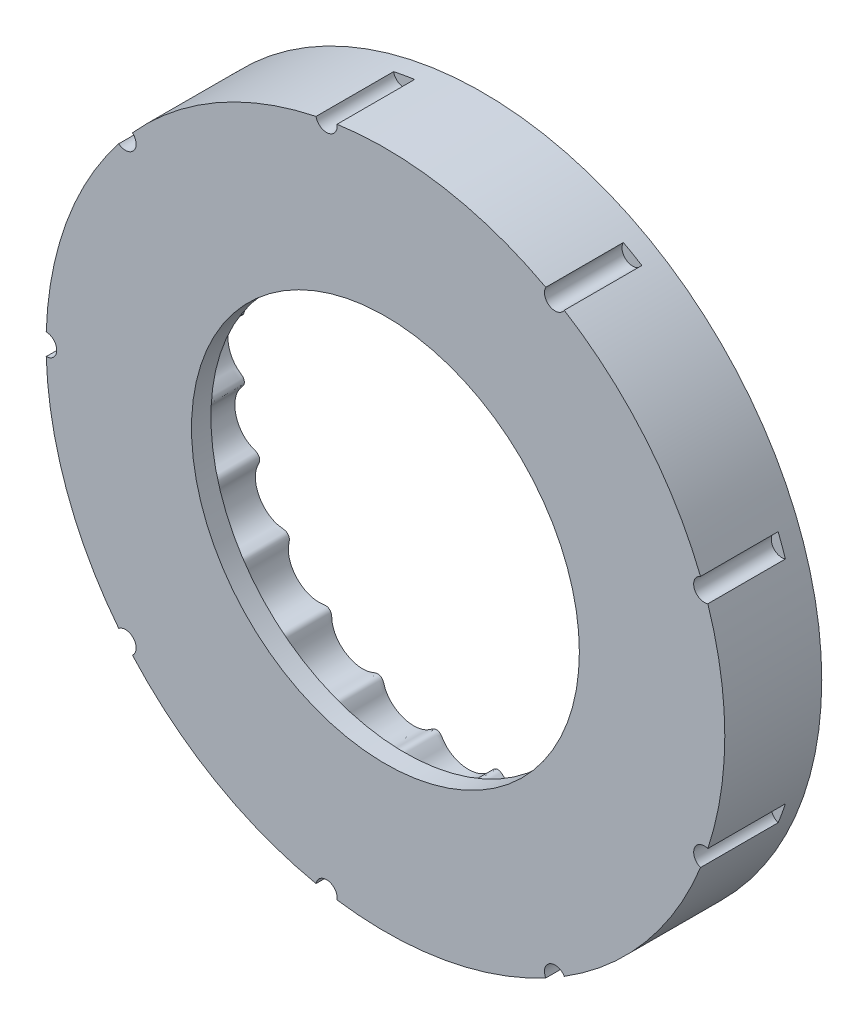
SolidWorks part; units mm, degrees
ref_plane "Plan de face" through (0, 0, 0) normal (0, 0, 1) x (1, 0, 0)
ref_plane "Plan de dessus" through (0, 0, 0) normal (0, 1, 0) x (1, 0, 0)
ref_plane "Plan de droite" through (0, 0, 0) normal (1, 0, 0) x (0, 0, -1)
sketch "Esquisse1" plane through (0, 0, 0) normal (0, 0, 1) x (1, 0, 0)
  line L0 (-1000, 0) -> (49000, 0) construction
  circle A1 centre (0, 0) radius 35
  spline S0 degree 4 poles (24.1426, 6.7991) (24.1177, 6.7609) (24.0692, 6.6836) (24.0004, 6.5645) (23.9483, 6.387) (23.9505, 6.1855) (24.0272, 5.9803) (24.1778, 5.8151) (24.3705, 5.7045) (24.5983, 5.5844) (24.8479, 5.4264) (25.1139, 5.2067) (25.3819, 4.9129) (25.6102, 4.583) (25.7961, 4.2235) (25.9371, 3.8403) (26.0305, 3.4429) (26.0756, 3.0373) (26.0716, 2.6291) (26.0179, 2.2244) (25.9151, 1.834) (25.7643, 1.4641) (25.5917, 1.1641) (25.4167, 0.9296) (25.2526, 0.7496) (25.1124, 0.6144) (24.9828, 0.4987) (24.8797, 0.3844) (24.8179, 0.2829) (24.7848, 0.2051) (24.7673, 0.1461) (24.7588, 0.1043) (24.7529, 0.0597) (24.7496, 0.0145) (24.7496, -0.0147) (24.7529, -0.06) (24.7589, -0.1048) (24.7675, -0.1468) (24.7852, -0.2061) (24.8185, -0.2842) (24.8808, -0.3859) (24.9847, -0.5005) (25.1148, -0.6166) (25.2554, -0.7525) (25.4198, -0.9333) (25.595, -1.1691) (25.7689, -1.4729) (25.9207, -1.8497) (26.0235, -2.2499) (26.0747, -2.6669) (26.0733, -3.0863) (26.0204, -3.5015) (25.917, -3.9063) (25.7644, -4.2943) (25.5662, -4.6548) (25.3259, -4.9815) (25.0816, -5.2331) (24.8519, -5.4186) (24.6671, -5.5402) (24.5395, -5.6139) (24.4102, -5.6846) (24.274, -5.758) (24.12, -5.8678) (23.9899, -6.0503) (23.9364, -6.2751) (23.9692, -6.4958) (24.0654, -6.6843) (24.1784, -6.8519) (24.2801, -7.019) (24.3936, -7.2353) (24.5034, -7.5077) (24.5951, -7.8454) (24.647, -8.2482) (24.6457, -8.6612) (24.576, -9.1855) (24.4176, -9.6961) (24.1747, -10.1766) (23.852, -10.6101) (23.5588, -10.9098) (23.241, -11.1578) (22.9466, -11.3291) (22.6921, -11.4408) (22.4727, -11.5135) (22.2939, -11.5615) (22.1013, -11.606) (21.9021, -11.6816) (21.7285, -11.8281) (21.6209, -12.0388) (21.6016, -12.2637) (21.6505, -12.4693) (21.7183, -12.6598) (21.7746, -12.8471) (21.8297, -13.085) (21.8672, -13.3762) (21.8707, -13.726) (21.8195, -14.1287) (21.7142, -14.528) (21.5148, -15.0178) (21.2331, -15.4721) (20.8771, -15.876) (20.4557, -16.2144) (20.0964, -16.4307) (19.7262, -16.5906) (19.3981, -16.6821) (19.1236, -16.7259) (18.8929, -16.7409) (18.7078, -16.7424) (18.5101, -16.7378) (18.2984, -16.7644) (18.0955, -16.8669) (17.9421, -17.0472) (17.8714, -17.2614) (17.8702, -17.4725) (17.8883, -17.6738) (17.8957, -17.8692) (17.8889, -18.1133) (17.8517, -18.4044) (17.7668, -18.7438) (17.6158, -19.1205) (17.4134, -19.4803) (17.1623, -19.8168) (16.8685, -20.1221) (16.5358, -20.3908) (16.1684, -20.6173) (15.771, -20.7957) (15.3688, -20.9145) (14.9702, -20.976) (14.6296, -20.9817) (14.3529, -20.9549) (14.1259, -20.9112) (13.9464, -20.866) (13.7558, -20.8128) (13.5435, -20.7889) (13.3222, -20.8417) (13.1314, -20.9817) (13.013, -21.1736) (12.9618, -21.3782) (12.9291, -21.5776) (12.887, -21.7685) (12.8188, -22.0029) (12.7093, -22.2752) (12.5416, -22.5821) (12.3006, -22.9086) (12.0142, -23.2057) (11.6866, -23.4682) (11.3255, -23.6897) (10.9359, -23.8661) (10.5233, -23.9928) (10.0937, -24.0655) (9.6744, -24.0792) (9.2731, -24.0382) (8.942, -23.9578) (8.6811, -23.862) (8.4724, -23.7624) (8.31, -23.6735) (8.1383, -23.575) (7.9372, -23.5018) (7.7049, -23.5021) (7.4781, -23.6007) (7.3169, -23.7729) (7.2208, -23.9706) (7.1156, -24.2034) (6.9743, -24.4604) (6.773, -24.7375) (6.4979, -25.0224) (6.1834, -25.2709) (5.8357, -25.4797) (5.4603, -25.6452) (5.0615, -25.7656) (4.6447, -25.8371) (4.2157, -25.8559) (3.7816, -25.8181) (3.3723, -25.7258) (2.9942, -25.5849) (2.6941, -25.4236) (2.4656, -25.2649) (2.2891, -25.1158) (2.1537, -24.9891) (2.0123, -24.8511) (1.8324, -24.7331) (1.553, -24.6659) (1.2621, -24.7546) (1.0754, -24.9576) (0.8891, -25.1941) (0.6967, -25.4018) (0.4476, -25.6153) (0.1257, -25.8218) (-0.2246, -25.9871) (-0.599, -26.1091) (-0.9909, -26.1853) (-1.3919, -26.2146) (-1.7962, -26.1958) (-2.1981, -26.1285) (-2.5915, -26.0119) (-2.9628, -25.849) (-3.3062, -25.6424) (-3.6154, -25.3948) (-3.8503, -25.1456) (-4.0231, -24.9087) (-4.157, -24.6911) (-4.2763, -24.5066) (-4.4563, -24.3545) (-4.6931, -24.2829) (-4.9238, -24.3097) (-5.115, -24.4061) (-5.2732, -24.5252) (-5.423, -24.6339) (-5.6174, -24.7592) (-5.864, -24.8876) (-6.1822, -25.0094) (-6.5751, -25.1011) (-6.9928, -25.1407) (-7.4281, -25.1231) (-7.8512, -25.0501) (-8.2556, -24.9263) (-8.636, -24.7563) (-8.9874, -24.5444) (-9.3058, -24.2932) (-9.5861, -24.0067) (-9.8229, -23.6892) (-9.9872, -23.3887) (-10.0948, -23.1158) (-10.1696, -22.8715) (-10.2411, -22.6635) (-10.3812, -22.4737) (-10.595, -22.3493) (-10.8256, -22.322) (-11.0338, -22.3709) (-11.2164, -22.4474) (-11.3887, -22.5149) (-11.6084, -22.5872) (-11.8793, -22.649) (-12.2179, -22.6866) (-12.6212, -22.6763) (-13.0353, -22.6095) (-13.4521, -22.4829) (-13.8453, -22.3049) (-14.2094, -22.0805) (-14.5395, -21.815) (-14.8313, -21.5131) (-15.0777, -21.1819) (-15.2753, -20.8275) (-15.4026, -20.5017) (-15.4765, -20.2177) (-15.5143, -19.9765) (-15.5318, -19.7817) (-15.5392, -19.5798) (-15.5656, -19.3704) (-15.6608, -19.166) (-15.8341, -19.0047) (-16.0476, -18.9266) (-16.2611, -18.9252) (-16.4568, -18.9543) (-16.6405, -18.9763) (-16.8713, -18.9908) (-17.1491, -18.9822) (-17.4862, -18.9332) (-17.8737, -18.8216) (-18.2576, -18.6527) (-18.6291, -18.4253) (-18.9648, -18.1541) (-19.2607, -17.8454) (-19.5135, -17.5053) (-19.7199, -17.1396) (-19.875, -16.7569) (-19.9769, -16.364) (-20.018, -16.0166) (-20.0178, -15.7231) (-19.9934, -15.4801) (-19.9613, -15.2872) (-19.9181, -15.0898) (-19.894, -14.8799) (-19.9394, -14.6589) (-20.0707, -14.462) (-20.2602, -14.3367) (-20.4672, -14.2852) (-20.6639, -14.2651) (-20.8473, -14.2402) (-21.0742, -14.196) (-21.3408, -14.1175) (-21.6546, -13.985) (-22.0015, -13.7794) (-22.3304, -13.5193) (-22.7055, -13.1302) (-23.0074, -12.6844) (-23.2291, -12.1981) (-23.3648, -11.6869) (-23.4186, -11.2774) (-23.4182, -10.8714) (-23.3703, -10.5248) (-23.296, -10.2407) (-23.211, -10.0117) (-23.1314, -9.8331) (-23.0402, -9.6526) (-22.9672, -9.4541) (-22.9601, -9.2287) (-23.0424, -9.0072) (-23.1982, -8.8407) (-23.3889, -8.7414) (-23.5777, -8.6723) (-23.7531, -8.5999) (-23.9662, -8.4963) (-24.2093, -8.3477) (-24.4803, -8.1356) (-24.7613, -7.8463) (-25.0085, -7.5133) (-25.2666, -7.049) (-25.4429, -6.5476) (-25.5339, -6.0256) (-25.5366, -5.4989) (-25.4855, -5.0889) (-25.3828, -4.696) (-25.2489, -4.3726) (-25.1052, -4.1164) (-24.9652, -3.9162) (-24.8431, -3.7634) (-24.7098, -3.6112) (-24.5919, -3.4354) (-24.5338, -3.2206) (-24.5604, -2.9926) (-24.6667, -2.797) (-24.8227, -2.6537) (-24.9897, -2.5393) (-25.1463, -2.4221) (-25.3325, -2.2638) (-25.5023, -2.0873) (-25.6545, -1.8958) (-25.7905, -1.6883) (-25.89, -1.512) (-25.979, -1.3255) (-26.0566, -1.1315) (-26.1214, -0.9307) (-26.1732, -0.7298) (-26.2073, -0.5457) (-26.2284, -0.3959) (-26.2405, -0.2557) (-26.247, -0.1691) (-26.2503, -0.0328) (-26.2503, 0.0323) (-26.2471, 0.1679) (-26.2407, 0.2542) (-26.2286, 0.3933) (-26.2078, 0.5423) (-26.1742, 0.7251) (-26.123, 0.925) (-26.0591, 1.1245) (-25.9824, 1.3176) (-25.8737, 1.547) (-25.7224, 1.8046) (-25.5451, 2.0414) (-25.3437, 2.2529) (-25.1596, 2.4115) (-25.0044, 2.5289) (-24.8386, 2.6423) (-24.6804, 2.7808) (-24.5546, 2.9935) (-24.5303, 3.2355) (-24.6, 3.4498) (-24.7118, 3.6094) (-24.804, 3.7191) (-24.9086, 3.8447) (-25.0204, 3.9911) (-25.1376, 4.1713) (-25.2521, 4.3886) (-25.3469, 4.6153) (-25.4409, 4.9075) (-25.515, 5.269) (-25.5464, 5.6988) (-25.509, 6.1899) (-25.401, 6.6704) (-25.2688, 7.0153) (-25.1588, 7.235) (-25.0985, 7.3418) knots 0 0 0 0 0 0.001685 0.003369 0.005054 0.006738 0.009006 0.011274 0.013086 0.014899 0.018524 0.022149 0.025774 0.029532 0.03329 0.037047 0.040805 0.044562 0.048319 0.052076 0.055834 0.059425 0.063017 0.064813 0.066609 0.068405 0.070201 0.071231 0.072261 0.072776 0.073291 0.073548 0.073806 0.074321 0.074838 0.075097 0.075356 0.075873 0.07639 0.077425 0.07846 0.080263 0.082066 0.083868 0.085671 0.089277 0.092883 0.09675 0.100617 0.104484 0.108351 0.112188 0.116026 0.119864 0.123701 0.127327 0.130952 0.132764 0.134577 0.135483 0.13639 0.138202 0.140296 0.142389 0.144459 0.146528 0.148331 0.150133 0.151935 0.153737 0.157342 0.160946 0.164812 0.168678 0.172544 0.180416 0.184421 0.188427 0.192432 0.195844 0.199256 0.200962 0.202668 0.204374 0.20608 0.208269 0.210458 0.212527 0.214596 0.216398 0.2182 0.220001 0.221803 0.225407 0.22901 0.232875 0.23674 0.240605 0.248477 0.252483 0.256489 0.260496 0.263908 0.26732 0.269026 0.270732 0.272438 0.274144 0.276335 0.278527 0.280595 0.282663 0.284464 0.286266 0.288067 0.289868 0.293471 0.297074 0.300938 0.304802 0.308666 0.31253 0.316537 0.320545 0.324552 0.328559 0.331971 0.335384 0.33709 0.338796 0.340502 0.342208 0.344401 0.346595 0.348662 0.350729 0.35253 0.354331 0.356132 0.357933 0.361536 0.365138 0.369001 0.372864 0.376727 0.38059 0.384598 0.388606 0.392614 0.396623 0.400035 0.403448 0.405154 0.40686 0.408567 0.410273 0.412468 0.414663 0.416905 0.419148 0.420948 0.422747 0.426346 0.429946 0.433545 0.437321 0.441097 0.444873 0.44865 0.452659 0.456668 0.460677 0.464686 0.468099 0.471512 0.473218 0.474925 0.476631 0.478338 0.480534 0.48273 0.48702 0.488749 0.490478 0.493937 0.497395 0.500854 0.50453 0.508207 0.511883 0.515559 0.519335 0.523111 0.526887 0.530662 0.534262 0.537861 0.54146 0.543259 0.545059 0.547301 0.549542 0.551738 0.553933 0.55564 0.557346 0.559053 0.560759 0.564172 0.567585 0.571593 0.575602 0.57961 0.583619 0.587396 0.591172 0.594949 0.598726 0.602325 0.605924 0.609523 0.611323 0.613123 0.615366 0.61761 0.619804 0.621998 0.623704 0.625411 0.627117 0.628823 0.632235 0.635648 0.639656 0.643663 0.647671 0.651679 0.655542 0.659406 0.663269 0.667133 0.670735 0.674338 0.676139 0.67794 0.679742 0.681543 0.68361 0.685678 0.68787 0.690063 0.691769 0.693475 0.695181 0.696887 0.700299 0.703711 0.707718 0.711725 0.715732 0.719739 0.723603 0.727468 0.731332 0.735197 0.7388 0.742403 0.744204 0.746006 0.747808 0.749609 0.751678 0.753746 0.755937 0.758127 0.759833 0.761539 0.763245 0.764951 0.768363 0.771775 0.775781 0.779787 0.783793 0.791664 0.795529 0.799395 0.80326 0.806864 0.810468 0.81227 0.814073 0.815875 0.817677 0.819746 0.821815 0.823999 0.826183 0.827931 0.82968 0.831429 0.833177 0.836675 0.840172 0.844094 0.848015 0.851937 0.859725 0.863591 0.867458 0.871324 0.874929 0.878534 0.880337 0.882139 0.883942 0.885745 0.887814 0.889884 0.891953 0.894023 0.895826 0.897629 0.899432 0.901235 0.904841 0.906644 0.908448 0.910381 0.912315 0.914249 0.916183 0.918117 0.92005 0.921017 0.921984 0.922951 0.923918 0.924879 0.925839 0.9268 0.927761 0.929682 0.931604 0.933525 0.935447 0.937368 0.93929 0.942875 0.94646 0.948253 0.950045 0.951838 0.95363 0.955683 0.957735 0.960756 0.962266 0.963777 0.964909 0.96604 0.968304 0.970568 0.972832 0.975095 0.977359 0.981887 0.986415 0.990943 0.995472 1 1 1 1 1 construction
  spline S1 degree 4 poles (24.75, 0) (24.75, -0.0119) (24.7507, -0.0298) (24.7529, -0.06) (24.7589, -0.1048) (24.7675, -0.1468) (24.7852, -0.2061) (24.8185, -0.2842) (24.8808, -0.3859) (24.9847, -0.5005) (25.1148, -0.6166) (25.2554, -0.7525) (25.4198, -0.9333) (25.595, -1.1691) (25.7689, -1.4729) (25.9207, -1.8497) (26.0235, -2.2499) (26.0747, -2.6669) (26.0733, -3.0863) (26.0204, -3.5015) (25.917, -3.9063) (25.7644, -4.2943) (25.5662, -4.6548) (25.3259, -4.9815) (25.0816, -5.2331) (24.8519, -5.4186) (24.6671, -5.5402) (24.5395, -5.6139) (24.4102, -5.6846) (24.274, -5.758) (24.12, -5.8678) (23.9899, -6.0503) (23.9364, -6.2751) (23.9692, -6.4958) (24.0654, -6.6843) (24.1784, -6.8519) (24.2801, -7.019) (24.3936, -7.2353) (24.5034, -7.5077) (24.5951, -7.8454) (24.647, -8.2482) (24.6457, -8.6612) (24.576, -9.1855) (24.4176, -9.6961) (24.1747, -10.1766) (23.852, -10.6101) (23.5588, -10.9098) (23.241, -11.1578) (22.9466, -11.3291) (22.6921, -11.4408) (22.4727, -11.5135) (22.2939, -11.5615) (22.1013, -11.606) (21.9021, -11.6816) (21.7285, -11.8281) (21.6209, -12.0388) (21.6016, -12.2637) (21.6505, -12.4693) (21.7183, -12.6598) (21.7746, -12.8471) (21.8297, -13.085) (21.8672, -13.3762) (21.8707, -13.726) (21.8195, -14.1287) (21.7142, -14.528) (21.5148, -15.0178) (21.2331, -15.4721) (20.8771, -15.876) (20.4557, -16.2144) (20.0964, -16.4307) (19.7262, -16.5906) (19.3981, -16.6821) (19.1236, -16.7259) (18.8929, -16.7409) (18.7078, -16.7424) (18.5101, -16.7378) (18.2984, -16.7644) (18.0955, -16.8669) (17.9421, -17.0472) (17.8714, -17.2614) (17.8702, -17.4725) (17.8883, -17.6738) (17.8957, -17.8692) (17.8889, -18.1133) (17.8517, -18.4044) (17.7668, -18.7438) (17.6158, -19.1205) (17.4134, -19.4803) (17.1623, -19.8168) (16.8685, -20.1221) (16.5358, -20.3908) (16.1684, -20.6173) (15.771, -20.7957) (15.3688, -20.9145) (14.9702, -20.976) (14.6296, -20.9817) (14.3529, -20.9549) (14.1259, -20.9112) (13.9464, -20.866) (13.7558, -20.8128) (13.5435, -20.7889) (13.3222, -20.8417) (13.1314, -20.9817) (13.013, -21.1736) (12.9618, -21.3782) (12.9291, -21.5776) (12.887, -21.7685) (12.8188, -22.0029) (12.7093, -22.2752) (12.5416, -22.5821) (12.3006, -22.9086) (12.0142, -23.2057) (11.6866, -23.4682) (11.3255, -23.6897) (10.9359, -23.8661) (10.5233, -23.9928) (10.0937, -24.0655) (9.6744, -24.0792) (9.2731, -24.0382) (8.942, -23.9578) (8.6811, -23.862) (8.4724, -23.7624) (8.31, -23.6735) (8.1383, -23.575) (7.9372, -23.5018) (7.7049, -23.5021) (7.4781, -23.6007) (7.3169, -23.7729) (7.2208, -23.9706) (7.1156, -24.2034) (6.9743, -24.4604) (6.773, -24.7375) (6.4979, -25.0224) (6.1834, -25.2709) (5.8357, -25.4797) (5.4603, -25.6452) (5.0615, -25.7656) (4.6447, -25.8371) (4.2157, -25.8559) (3.7816, -25.8181) (3.3723, -25.7258) (2.9942, -25.5849) (2.6941, -25.4236) (2.4656, -25.2649) (2.2891, -25.1158) (2.1537, -24.9891) (2.0123, -24.8511) (1.8324, -24.7331) (1.553, -24.6659) (1.2621, -24.7546) (1.0754, -24.9576) (0.8891, -25.1941) (0.6967, -25.4018) (0.4476, -25.6153) (0.1257, -25.8218) (-0.2246, -25.9871) (-0.599, -26.1091) (-0.9909, -26.1853) (-1.3919, -26.2146) (-1.7962, -26.1958) (-2.1981, -26.1285) (-2.5915, -26.0119) (-2.9628, -25.849) (-3.3062, -25.6424) (-3.6154, -25.3948) (-3.8503, -25.1456) (-4.0231, -24.9087) (-4.157, -24.6911) (-4.2763, -24.5066) (-4.4563, -24.3545) (-4.6931, -24.2829) (-4.9238, -24.3097) (-5.115, -24.4061) (-5.2732, -24.5252) (-5.423, -24.6339) (-5.6174, -24.7592) (-5.864, -24.8876) (-6.1822, -25.0094) (-6.5751, -25.1011) (-6.9928, -25.1407) (-7.4281, -25.1231) (-7.8512, -25.0501) (-8.2556, -24.9263) (-8.636, -24.7563) (-8.9874, -24.5444) (-9.3058, -24.2932) (-9.5861, -24.0067) (-9.8229, -23.6892) (-9.9872, -23.3887) (-10.0948, -23.1158) (-10.1696, -22.8715) (-10.2411, -22.6635) (-10.3812, -22.4737) (-10.595, -22.3493) (-10.8256, -22.322) (-11.0338, -22.3709) (-11.2164, -22.4474) (-11.3887, -22.5149) (-11.6084, -22.5872) (-11.8793, -22.649) (-12.2179, -22.6866) (-12.6212, -22.6763) (-13.0353, -22.6095) (-13.4521, -22.4829) (-13.8453, -22.3049) (-14.2094, -22.0805) (-14.5395, -21.815) (-14.8313, -21.5131) (-15.0777, -21.1819) (-15.2753, -20.8275) (-15.4026, -20.5017) (-15.4765, -20.2177) (-15.5143, -19.9765) (-15.5318, -19.7817) (-15.5392, -19.5798) (-15.5656, -19.3704) (-15.6608, -19.166) (-15.8341, -19.0047) (-16.0476, -18.9266) (-16.2611, -18.9252) (-16.4568, -18.9543) (-16.6405, -18.9763) (-16.8713, -18.9908) (-17.1491, -18.9822) (-17.4862, -18.9332) (-17.8737, -18.8216) (-18.2576, -18.6527) (-18.6291, -18.4253) (-18.9648, -18.1541) (-19.2607, -17.8454) (-19.5135, -17.5053) (-19.7199, -17.1396) (-19.875, -16.7569) (-19.9769, -16.364) (-20.018, -16.0166) (-20.0178, -15.7231) (-19.9934, -15.4801) (-19.9613, -15.2872) (-19.9181, -15.0898) (-19.894, -14.8799) (-19.9394, -14.6589) (-20.0707, -14.462) (-20.2602, -14.3367) (-20.4672, -14.2852) (-20.6639, -14.2651) (-20.8473, -14.2402) (-21.0742, -14.196) (-21.3408, -14.1175) (-21.6546, -13.985) (-22.0015, -13.7794) (-22.3304, -13.5193) (-22.7055, -13.1302) (-23.0074, -12.6844) (-23.2291, -12.1981) (-23.3648, -11.6869) (-23.4186, -11.2774) (-23.4182, -10.8714) (-23.3703, -10.5248) (-23.296, -10.2407) (-23.211, -10.0117) (-23.1314, -9.8331) (-23.0402, -9.6526) (-22.9672, -9.4541) (-22.9601, -9.2287) (-23.0424, -9.0072) (-23.1982, -8.8407) (-23.3889, -8.7414) (-23.5777, -8.6723) (-23.7531, -8.5999) (-23.9662, -8.4963) (-24.2093, -8.3477) (-24.4803, -8.1356) (-24.7613, -7.8463) (-25.0085, -7.5133) (-25.2666, -7.049) (-25.4429, -6.5476) (-25.5339, -6.0256) (-25.5366, -5.4989) (-25.4855, -5.0889) (-25.3828, -4.696) (-25.2489, -4.3726) (-25.1052, -4.1164) (-24.9652, -3.9162) (-24.8431, -3.7634) (-24.7098, -3.6112) (-24.5919, -3.4354) (-24.5338, -3.2206) (-24.5604, -2.9926) (-24.6667, -2.797) (-24.8227, -2.6537) (-24.9897, -2.5393) (-25.1463, -2.4221) (-25.3325, -2.2638) (-25.5023, -2.0873) (-25.6545, -1.8958) (-25.7905, -1.6883) (-25.89, -1.512) (-25.979, -1.3255) (-26.0566, -1.1315) (-26.1214, -0.9307) (-26.1732, -0.7298) (-26.2073, -0.5457) (-26.2284, -0.3959) (-26.2405, -0.2557) (-26.247, -0.1691) (-26.2495, -0.0667) (-26.25, -0.0223) (-26.25, 0) knots 0.074321 0.074321 0.074321 0.074321 0.074321 0.074838 0.075097 0.075356 0.075873 0.07639 0.077425 0.07846 0.080263 0.082066 0.083868 0.085671 0.089277 0.092883 0.09675 0.100617 0.104484 0.108351 0.112188 0.116026 0.119864 0.123701 0.127327 0.130952 0.132764 0.134577 0.135483 0.13639 0.138202 0.140296 0.142389 0.144459 0.146528 0.148331 0.150133 0.151935 0.153737 0.157342 0.160946 0.164812 0.168678 0.172544 0.180416 0.184421 0.188427 0.192432 0.195844 0.199256 0.200962 0.202668 0.204374 0.20608 0.208269 0.210458 0.212527 0.214596 0.216398 0.2182 0.220001 0.221803 0.225407 0.22901 0.232875 0.23674 0.240605 0.248477 0.252483 0.256489 0.260496 0.263908 0.26732 0.269026 0.270732 0.272438 0.274144 0.276335 0.278527 0.280595 0.282663 0.284464 0.286266 0.288067 0.289868 0.293471 0.297074 0.300938 0.304802 0.308666 0.31253 0.316537 0.320545 0.324552 0.328559 0.331971 0.335384 0.33709 0.338796 0.340502 0.342208 0.344401 0.346595 0.348662 0.350729 0.35253 0.354331 0.356132 0.357933 0.361536 0.365138 0.369001 0.372864 0.376727 0.38059 0.384598 0.388606 0.392614 0.396623 0.400035 0.403448 0.405154 0.40686 0.408567 0.410273 0.412468 0.414663 0.416905 0.419148 0.420948 0.422747 0.426346 0.429946 0.433545 0.437321 0.441097 0.444873 0.44865 0.452659 0.456668 0.460677 0.464686 0.468099 0.471512 0.473218 0.474925 0.476631 0.478338 0.480534 0.48273 0.48702 0.488749 0.490478 0.493937 0.497395 0.500854 0.50453 0.508207 0.511883 0.515559 0.519335 0.523111 0.526887 0.530662 0.534262 0.537861 0.54146 0.543259 0.545059 0.547301 0.549542 0.551738 0.553933 0.55564 0.557346 0.559053 0.560759 0.564172 0.567585 0.571593 0.575602 0.57961 0.583619 0.587396 0.591172 0.594949 0.598726 0.602325 0.605924 0.609523 0.611323 0.613123 0.615366 0.61761 0.619804 0.621998 0.623704 0.625411 0.627117 0.628823 0.632235 0.635648 0.639656 0.643663 0.647671 0.651679 0.655542 0.659406 0.663269 0.667133 0.670735 0.674338 0.676139 0.67794 0.679742 0.681543 0.68361 0.685678 0.68787 0.690063 0.691769 0.693475 0.695181 0.696887 0.700299 0.703711 0.707718 0.711725 0.715732 0.719739 0.723603 0.727468 0.731332 0.735197 0.7388 0.742403 0.744204 0.746006 0.747808 0.749609 0.751678 0.753746 0.755937 0.758127 0.759833 0.761539 0.763245 0.764951 0.768363 0.771775 0.775781 0.779787 0.783793 0.791664 0.795529 0.799395 0.80326 0.806864 0.810468 0.81227 0.814073 0.815875 0.817677 0.819746 0.821815 0.823999 0.826183 0.827931 0.82968 0.831429 0.833177 0.836675 0.840172 0.844094 0.848015 0.851937 0.859725 0.863591 0.867458 0.871324 0.874929 0.878534 0.880337 0.882139 0.883942 0.885745 0.887814 0.889884 0.891953 0.894023 0.895826 0.897629 0.899432 0.901235 0.904841 0.906644 0.908448 0.910381 0.912315 0.914249 0.916183 0.918117 0.92005 0.921017 0.921984 0.922951 0.923918 0.923918 0.923918 0.923918 0.923918
  spline S2 degree 4 poles (24.75, 0) (24.75, 0.0119) (24.7507, 0.0298) (24.7529, 0.06) (24.7589, 0.1048) (24.7675, 0.1468) (24.7852, 0.2061) (24.8185, 0.2842) (24.8808, 0.3859) (24.9847, 0.5005) (25.1148, 0.6166) (25.2554, 0.7525) (25.4198, 0.9333) (25.595, 1.1691) (25.7689, 1.4729) (25.9207, 1.8497) (26.0235, 2.2499) (26.0747, 2.6669) (26.0733, 3.0863) (26.0204, 3.5015) (25.917, 3.9063) (25.7644, 4.2943) (25.5662, 4.6548) (25.3259, 4.9815) (25.0816, 5.2331) (24.8519, 5.4186) (24.6671, 5.5402) (24.5395, 5.6139) (24.4102, 5.6846) (24.274, 5.758) (24.12, 5.8678) (23.9899, 6.0503) (23.9364, 6.2751) (23.9692, 6.4958) (24.0654, 6.6843) (24.1784, 6.8519) (24.2801, 7.019) (24.3936, 7.2353) (24.5034, 7.5077) (24.5951, 7.8454) (24.647, 8.2482) (24.6457, 8.6612) (24.576, 9.1855) (24.4176, 9.6961) (24.1747, 10.1766) (23.852, 10.6101) (23.5588, 10.9098) (23.241, 11.1578) (22.9466, 11.3291) (22.6921, 11.4408) (22.4727, 11.5135) (22.2939, 11.5615) (22.1013, 11.606) (21.9021, 11.6816) (21.7285, 11.8281) (21.6209, 12.0388) (21.6016, 12.2637) (21.6505, 12.4693) (21.7183, 12.6598) (21.7746, 12.8471) (21.8297, 13.085) (21.8672, 13.3762) (21.8707, 13.726) (21.8195, 14.1287) (21.7142, 14.528) (21.5148, 15.0178) (21.2331, 15.4721) (20.8771, 15.876) (20.4557, 16.2144) (20.0964, 16.4307) (19.7262, 16.5906) (19.3981, 16.6821) (19.1236, 16.7259) (18.8929, 16.7409) (18.7078, 16.7424) (18.5101, 16.7378) (18.2984, 16.7644) (18.0955, 16.8669) (17.9421, 17.0472) (17.8714, 17.2614) (17.8702, 17.4725) (17.8883, 17.6738) (17.8957, 17.8692) (17.8889, 18.1133) (17.8517, 18.4044) (17.7668, 18.7438) (17.6158, 19.1205) (17.4134, 19.4803) (17.1623, 19.8168) (16.8685, 20.1221) (16.5358, 20.3908) (16.1684, 20.6173) (15.771, 20.7957) (15.3688, 20.9145) (14.9702, 20.976) (14.6296, 20.9817) (14.3529, 20.9549) (14.1259, 20.9112) (13.9464, 20.866) (13.7558, 20.8128) (13.5435, 20.7889) (13.3222, 20.8417) (13.1314, 20.9817) (13.013, 21.1736) (12.9618, 21.3782) (12.9291, 21.5776) (12.887, 21.7685) (12.8188, 22.0029) (12.7093, 22.2752) (12.5416, 22.5821) (12.3006, 22.9086) (12.0142, 23.2057) (11.6866, 23.4682) (11.3255, 23.6897) (10.9359, 23.8661) (10.5233, 23.9928) (10.0937, 24.0655) (9.6744, 24.0792) (9.2731, 24.0382) (8.942, 23.9578) (8.6811, 23.862) (8.4724, 23.7624) (8.31, 23.6735) (8.1383, 23.575) (7.9372, 23.5018) (7.7049, 23.5021) (7.4781, 23.6007) (7.3169, 23.7729) (7.2208, 23.9706) (7.1156, 24.2034) (6.9743, 24.4604) (6.773, 24.7375) (6.4979, 25.0224) (6.1834, 25.2709) (5.8357, 25.4797) (5.4603, 25.6452) (5.0615, 25.7656) (4.6447, 25.8371) (4.2157, 25.8559) (3.7816, 25.8181) (3.3723, 25.7258) (2.9942, 25.5849) (2.6941, 25.4236) (2.4656, 25.2649) (2.2891, 25.1158) (2.1537, 24.9891) (2.0123, 24.8511) (1.8324, 24.7331) (1.553, 24.6659) (1.2621, 24.7546) (1.0754, 24.9576) (0.8891, 25.1941) (0.6967, 25.4018) (0.4476, 25.6153) (0.1257, 25.8218) (-0.2246, 25.9871) (-0.599, 26.1091) (-0.9909, 26.1853) (-1.3919, 26.2146) (-1.7962, 26.1958) (-2.1981, 26.1285) (-2.5915, 26.0119) (-2.9628, 25.849) (-3.3062, 25.6424) (-3.6154, 25.3948) (-3.8503, 25.1456) (-4.0231, 24.9087) (-4.157, 24.6911) (-4.2763, 24.5066) (-4.4563, 24.3545) (-4.6931, 24.2829) (-4.9238, 24.3097) (-5.115, 24.4061) (-5.2732, 24.5252) (-5.423, 24.6339) (-5.6174, 24.7592) (-5.864, 24.8876) (-6.1822, 25.0094) (-6.5751, 25.1011) (-6.9928, 25.1407) (-7.4281, 25.1231) (-7.8512, 25.0501) (-8.2556, 24.9263) (-8.636, 24.7563) (-8.9874, 24.5444) (-9.3058, 24.2932) (-9.5861, 24.0067) (-9.8229, 23.6892) (-9.9872, 23.3887) (-10.0948, 23.1158) (-10.1696, 22.8715) (-10.2411, 22.6635) (-10.3812, 22.4737) (-10.595, 22.3493) (-10.8256, 22.322) (-11.0338, 22.3709) (-11.2164, 22.4474) (-11.3887, 22.5149) (-11.6084, 22.5872) (-11.8793, 22.649) (-12.2179, 22.6866) (-12.6212, 22.6763) (-13.0353, 22.6095) (-13.4521, 22.4829) (-13.8453, 22.3049) (-14.2094, 22.0805) (-14.5395, 21.815) (-14.8313, 21.5131) (-15.0777, 21.1819) (-15.2753, 20.8275) (-15.4026, 20.5017) (-15.4765, 20.2177) (-15.5143, 19.9765) (-15.5318, 19.7817) (-15.5392, 19.5798) (-15.5656, 19.3704) (-15.6608, 19.166) (-15.8341, 19.0047) (-16.0476, 18.9266) (-16.2611, 18.9252) (-16.4568, 18.9543) (-16.6405, 18.9763) (-16.8713, 18.9908) (-17.1491, 18.9822) (-17.4862, 18.9332) (-17.8737, 18.8216) (-18.2576, 18.6527) (-18.6291, 18.4253) (-18.9648, 18.1541) (-19.2607, 17.8454) (-19.5135, 17.5053) (-19.7199, 17.1396) (-19.875, 16.7569) (-19.9769, 16.364) (-20.018, 16.0166) (-20.0178, 15.7231) (-19.9934, 15.4801) (-19.9613, 15.2872) (-19.9181, 15.0898) (-19.894, 14.8799) (-19.9394, 14.6589) (-20.0707, 14.462) (-20.2602, 14.3367) (-20.4672, 14.2852) (-20.6639, 14.2651) (-20.8473, 14.2402) (-21.0742, 14.196) (-21.3408, 14.1175) (-21.6546, 13.985) (-22.0015, 13.7794) (-22.3304, 13.5193) (-22.7055, 13.1302) (-23.0074, 12.6844) (-23.2291, 12.1981) (-23.3648, 11.6869) (-23.4186, 11.2774) (-23.4182, 10.8714) (-23.3703, 10.5248) (-23.296, 10.2407) (-23.211, 10.0117) (-23.1314, 9.8331) (-23.0402, 9.6526) (-22.9672, 9.4541) (-22.9601, 9.2287) (-23.0424, 9.0072) (-23.1982, 8.8407) (-23.3889, 8.7414) (-23.5777, 8.6723) (-23.7531, 8.5999) (-23.9662, 8.4963) (-24.2093, 8.3477) (-24.4803, 8.1356) (-24.7613, 7.8463) (-25.0085, 7.5133) (-25.2666, 7.049) (-25.4429, 6.5476) (-25.5339, 6.0256) (-25.5366, 5.4989) (-25.4855, 5.0889) (-25.3828, 4.696) (-25.2489, 4.3726) (-25.1052, 4.1164) (-24.9652, 3.9162) (-24.8431, 3.7634) (-24.7098, 3.6112) (-24.5919, 3.4354) (-24.5338, 3.2206) (-24.5604, 2.9926) (-24.6667, 2.797) (-24.8227, 2.6537) (-24.9897, 2.5393) (-25.1463, 2.4221) (-25.3325, 2.2638) (-25.5023, 2.0873) (-25.6545, 1.8958) (-25.7905, 1.6883) (-25.89, 1.512) (-25.979, 1.3255) (-26.0566, 1.1315) (-26.1214, 0.9307) (-26.1732, 0.7298) (-26.2073, 0.5457) (-26.2284, 0.3959) (-26.2405, 0.2557) (-26.247, 0.1691) (-26.2495, 0.0667) (-26.25, 0.0223) (-26.25, 0) knots 0.074321 0.074321 0.074321 0.074321 0.074321 0.074838 0.075097 0.075356 0.075873 0.07639 0.077425 0.07846 0.080263 0.082066 0.083868 0.085671 0.089277 0.092883 0.09675 0.100617 0.104484 0.108351 0.112188 0.116026 0.119864 0.123701 0.127327 0.130952 0.132764 0.134577 0.135483 0.13639 0.138202 0.140296 0.142389 0.144459 0.146528 0.148331 0.150133 0.151935 0.153737 0.157342 0.160946 0.164812 0.168678 0.172544 0.180416 0.184421 0.188427 0.192432 0.195844 0.199256 0.200962 0.202668 0.204374 0.20608 0.208269 0.210458 0.212527 0.214596 0.216398 0.2182 0.220001 0.221803 0.225407 0.22901 0.232875 0.23674 0.240605 0.248477 0.252483 0.256489 0.260496 0.263908 0.26732 0.269026 0.270732 0.272438 0.274144 0.276335 0.278527 0.280595 0.282663 0.284464 0.286266 0.288067 0.289868 0.293471 0.297074 0.300938 0.304802 0.308666 0.31253 0.316537 0.320545 0.324552 0.328559 0.331971 0.335384 0.33709 0.338796 0.340502 0.342208 0.344401 0.346595 0.348662 0.350729 0.35253 0.354331 0.356132 0.357933 0.361536 0.365138 0.369001 0.372864 0.376727 0.38059 0.384598 0.388606 0.392614 0.396623 0.400035 0.403448 0.405154 0.40686 0.408567 0.410273 0.412468 0.414663 0.416905 0.419148 0.420948 0.422747 0.426346 0.429946 0.433545 0.437321 0.441097 0.444873 0.44865 0.452659 0.456668 0.460677 0.464686 0.468099 0.471512 0.473218 0.474925 0.476631 0.478338 0.480534 0.48273 0.48702 0.488749 0.490478 0.493937 0.497395 0.500854 0.50453 0.508207 0.511883 0.515559 0.519335 0.523111 0.526887 0.530662 0.534262 0.537861 0.54146 0.543259 0.545059 0.547301 0.549542 0.551738 0.553933 0.55564 0.557346 0.559053 0.560759 0.564172 0.567585 0.571593 0.575602 0.57961 0.583619 0.587396 0.591172 0.594949 0.598726 0.602325 0.605924 0.609523 0.611323 0.613123 0.615366 0.61761 0.619804 0.621998 0.623704 0.625411 0.627117 0.628823 0.632235 0.635648 0.639656 0.643663 0.647671 0.651679 0.655542 0.659406 0.663269 0.667133 0.670735 0.674338 0.676139 0.67794 0.679742 0.681543 0.68361 0.685678 0.68787 0.690063 0.691769 0.693475 0.695181 0.696887 0.700299 0.703711 0.707718 0.711725 0.715732 0.719739 0.723603 0.727468 0.731332 0.735197 0.7388 0.742403 0.744204 0.746006 0.747808 0.749609 0.751678 0.753746 0.755937 0.758127 0.759833 0.761539 0.763245 0.764951 0.768363 0.771775 0.775781 0.779787 0.783793 0.791664 0.795529 0.799395 0.80326 0.806864 0.810468 0.81227 0.814073 0.815875 0.817677 0.819746 0.821815 0.823999 0.826183 0.827931 0.82968 0.831429 0.833177 0.836675 0.840172 0.844094 0.848015 0.851937 0.859725 0.863591 0.867458 0.871324 0.874929 0.878534 0.880337 0.882139 0.883942 0.885745 0.887814 0.889884 0.891953 0.894023 0.895826 0.897629 0.899432 0.901235 0.904841 0.906644 0.908448 0.910381 0.912315 0.914249 0.916183 0.918117 0.92005 0.921017 0.921984 0.922951 0.923918 0.923918 0.923918 0.923918 0.923918
  dimension "D1" = 70
extrude "Boss.-Extru.1" add sketch "Esquisse1" along normal blind 8
sketch "Esquisse3" plane through (0, 0, 8) normal (0, 0, 1) x (1, 0, 0)
  circle A0 centre (0, 0) radius 20
  circle A1 centre (0, 0) radius 35
  circle A2 centre (0, 0) radius 35 construction
  dimension "D1" = 40
extrude "Boss.-Extru.2" add sketch "Esquisse3" along normal blind 2
sketch "Esquisse4" plane through (0, 0, 10) normal (0, 0, 1) x (1, 0, 0)
  circle A0 centre (-35, 0) radius 1.1
  circle A1 centre (0, 0) radius 35 construction
  circle A2 centre (-26.8116, 22.4976) radius 1.1
  circle A3 centre (-6.0777, 34.4683) radius 1.1
  circle A4 centre (17.5, 30.3109) radius 1.1
  circle A5 centre (32.8892, 11.9707) radius 1.1
  circle A6 centre (32.8892, -11.9707) radius 1.1
  circle A7 centre (17.5, -30.3109) radius 1.1
  circle A8 centre (-6.0777, -34.4683) radius 1.1
  circle A9 centre (-26.8116, -22.4976) radius 1.1
  point P24 (0, 0)
  dimension "D1" = 2.2
extrude "Enlèv. mat.-Extru.2" cut sketch "Esquisse4" against normal blind 8
equation "\"R\"= 26'Radius of the rotor"
equation "\"E\"= 0.75'Eccentricity from input shaft to center of rotor"
equation "\"Rr\"= 0.5'Roller radius"
equation "\"N\"= 26'Amount of rollers"
